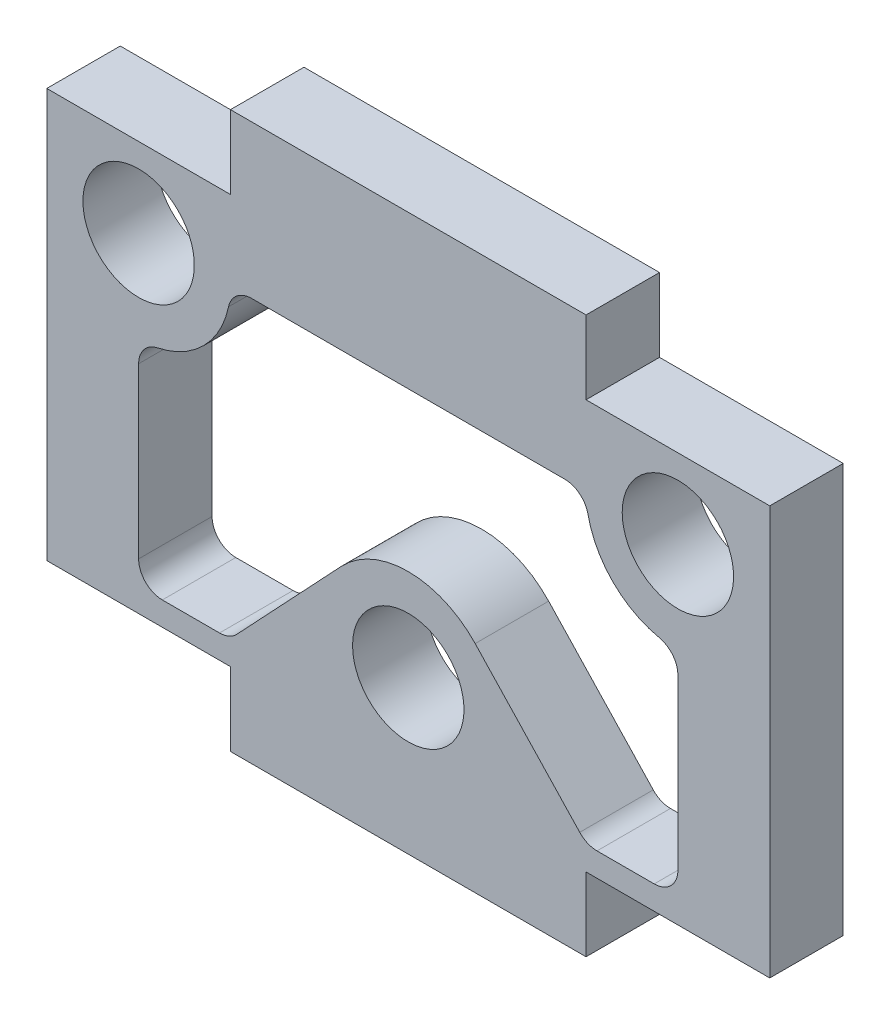
SolidWorks part; units mm, degrees
ref_plane "Front Plane" through (0, 0, 0) normal (0, 0, 1) x (1, 0, 0)
ref_plane "Top Plane" through (0, 0, 0) normal (0, 1, 0) x (1, 0, 0)
ref_plane "Right Plane" through (0, 0, 0) normal (1, 0, 0) x (0, 0, -1)
sketch "Sketch1" plane through (0, 0, 0) normal (0, 0, 1) x (1, 0, 0)
  line L0 (-25.7632, 28.4085) -> (-25.7632, 13.1585) construction
  line L1 (-33.2632, 29.4085) -> (-41.0132, 29.4085)
  line L2 (-41.0132, 29.4085) -> (-41.0132, 12.1585)
  line L3 (-33.2632, 29.4085) -> (-41.0132, 29.4085) construction
  line L4 (-41.0132, 12.1585) -> (-33.2632, 12.1585)
  line L5 (-37.1382, 21.2872) -> (-37.1382, 14.1585)
  line L6 (-22.9404, 18.1633) -> (-18.5296, 13.4734)
  line L7 (-18.2632, 29.4085) -> (-10.5132, 29.4085) construction
  line L8 (-18.2632, 12.1585) -> (-10.5132, 12.1585)
  line L9 (-33.2632, 29.4085) -> (-33.2632, 32.5085)
  line L10 (-33.2632, 32.5085) -> (-18.2632, 32.5085)
  line L11 (-18.2632, 29.4085) -> (-18.2632, 32.5085)
  line L12 (-14.3882, 21.2872) -> (-14.3882, 14.1585)
  line L13 (-33.2632, 12.1585) -> (-33.2632, 9.0585)
  line L14 (-10.5132, 12.1585) -> (-10.5132, 29.4085)
  line L15 (-10.5132, 20.7835) -> (-41.0132, 20.7835) construction
  line L16 (-18.2632, 12.1585) -> (-18.2632, 9.0585)
  line L17 (-33.2632, 9.0585) -> (-18.2632, 9.0585)
  line L18 (-10.5132, 29.4085) -> (-18.2632, 29.4085)
  line L19 (-36.1382, 13.1585) -> (-33.7251, 13.1585)
  line L20 (-32.3668, 26.0585) -> (-19.1595, 26.0585)
  line L21 (-32.9967, 13.4734) -> (-28.5859, 18.1633)
  line L22 (-17.8012, 13.1585) -> (-15.3882, 13.1585)
  circle A0 centre (-14.3882, 26.0585) radius 2.35
  circle A1 centre (-37.1382, 26.0585) radius 2.35
  circle A3 centre (-25.7632, 15.5085) radius 2.35
  arc A4 (-28.5859, 18.1633) -> (-22.9404, 18.1633) centre (-25.7632, 15.5085) cw
  arc A5 (-33.3456, 25.2636) -> (-36.3433, 22.2659) centre (-37.1382, 26.0585) cw
  arc A6 (-15.183, 22.2659) -> (-18.1808, 25.2636) centre (-14.3882, 26.0585) cw
  arc A7 (-37.1382, 21.2872) -> (-36.3433, 22.2659) centre (-36.1382, 21.2872) cw
  arc A8 (-32.3668, 26.0585) -> (-33.3456, 25.2636) centre (-32.3668, 25.0585) ccw
  arc A9 (-33.7251, 13.1585) -> (-32.9967, 13.4734) centre (-33.7251, 14.1585) ccw
  arc A10 (-18.1808, 25.2636) -> (-19.1595, 26.0585) centre (-19.1595, 25.0585) ccw
  arc A11 (-14.3882, 21.2872) -> (-15.183, 22.2659) centre (-15.3882, 21.2872) ccw
  arc A12 (-14.3882, 14.1585) -> (-15.3882, 13.1585) centre (-15.3882, 14.1585) cw
  arc A13 (-17.8012, 13.1585) -> (-18.5296, 13.4734) centre (-17.8012, 14.1585) cw
  arc A14 (-36.1382, 13.1585) -> (-37.1382, 14.1585) centre (-36.1382, 14.1585) cw
  point P45 (-14.3882, 13.1585)
  point P49 (-28.8442, 13.1585)
  point P52 (-37.1382, 13.1585)
  point P55 (-18.2335, 13.1585)
  dimension "D7" = 4.7
  dimension "D3" = 15.25
  dimension "D4" = 3.1
  dimension "D5" = 15
extrude "Extrude1" add sketch "Sketch1" along normal blind 3.1
